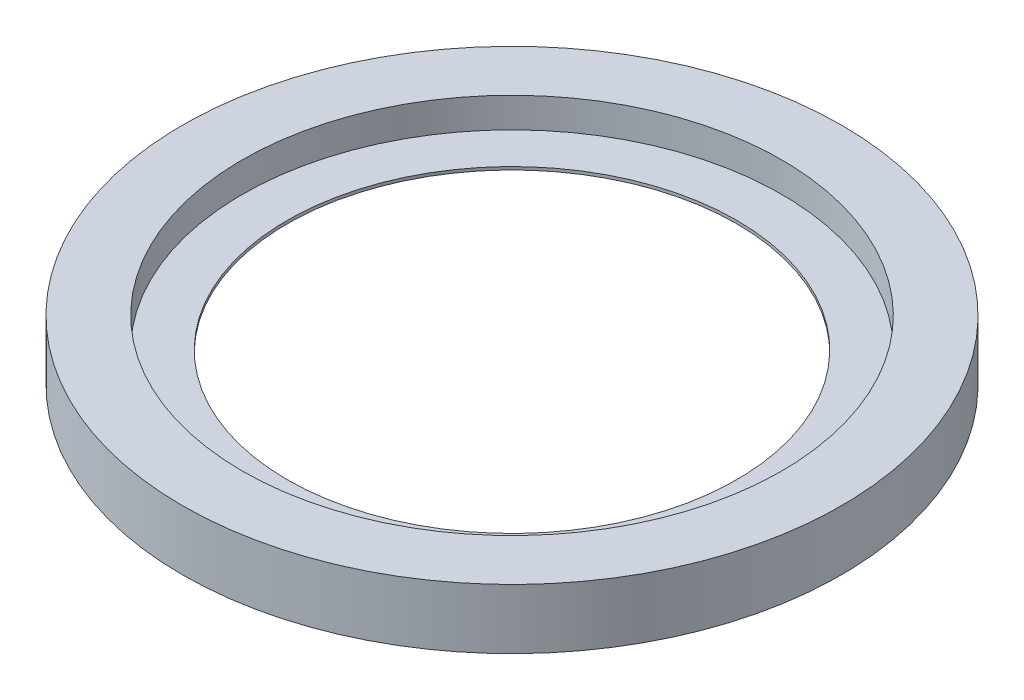
SolidWorks part; units mm, degrees
material "NBR"
ref_plane "Front Plane" through (0, 0, 0) normal (0, 0, 1) x (1, 0, 0)
ref_plane "Top Plane" through (0, 0, 0) normal (0, 1, 0) x (1, 0, 0)
ref_plane "Right Plane" through (0, 0, 0) normal (1, 0, 0) x (0, 0, -1)
sketch "Sketch1" plane through (0, 0, 0) normal (0, 1, 0) x (1, 0, 0)
  circle A0 centre (0, 0) radius 11
  circle A1 centre (0, 0) radius 9
  dimension "D1" = 22
  dimension "D2" = 2
extrude "Boss-Extrude1" add sketch "Sketch1" along normal blind 2
sketch "Sketch3" plane through (0, 2, 0) normal (0, 1, 0) x (1, 0, 0)
  circle A0 centre (0, 0) radius 9
  circle A1 centre (0, 0) radius 7.5
  dimension "D1" = 15
extrude "Boss-Extrude2" add sketch "Sketch3" against normal blind 0.1 from offset 1
